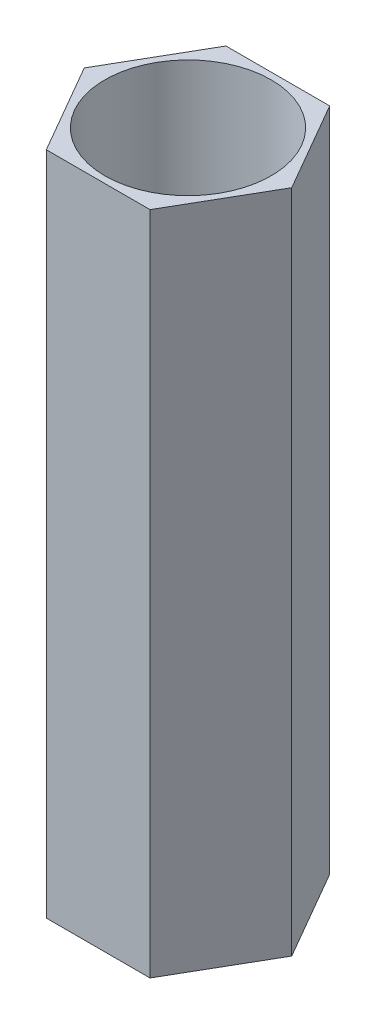
SolidWorks part; units mm, degrees
ref_plane "Front Plane" through (0, 0, 0) normal (0, 0, 1) x (1, 0, 0)
ref_plane "Top Plane" through (0, 0, 0) normal (0, 1, 0) x (1, 0, 0)
ref_plane "Right Plane" through (0, 0, 0) normal (1, 0, 0) x (0, 0, -1)
sketch "Sketch1" plane through (0, 0, 0) normal (0, 1, 0) x (1, 0, 0)
  line L1 (0.7794, -1.35) -> (1.5588, 0)
  line L2 (1.5588, 0) -> (0.7794, 1.35)
  line L3 (0.7794, 1.35) -> (-0.7794, 1.35)
  line L4 (-0.7794, 1.35) -> (-1.5588, 0)
  line L5 (-1.5588, 0) -> (-0.7794, -1.35)
  line L6 (-0.7794, -1.35) -> (0.7794, -1.35)
  circle A0 centre (0, 0) radius 1.35 construction
  circle A1 centre (0, 0) radius 1.25
  dimension "D1" = 2.7
  dimension "D2" = 2.5
extrude "Boss-Extrude1" add sketch "Sketch1" along normal blind 10
